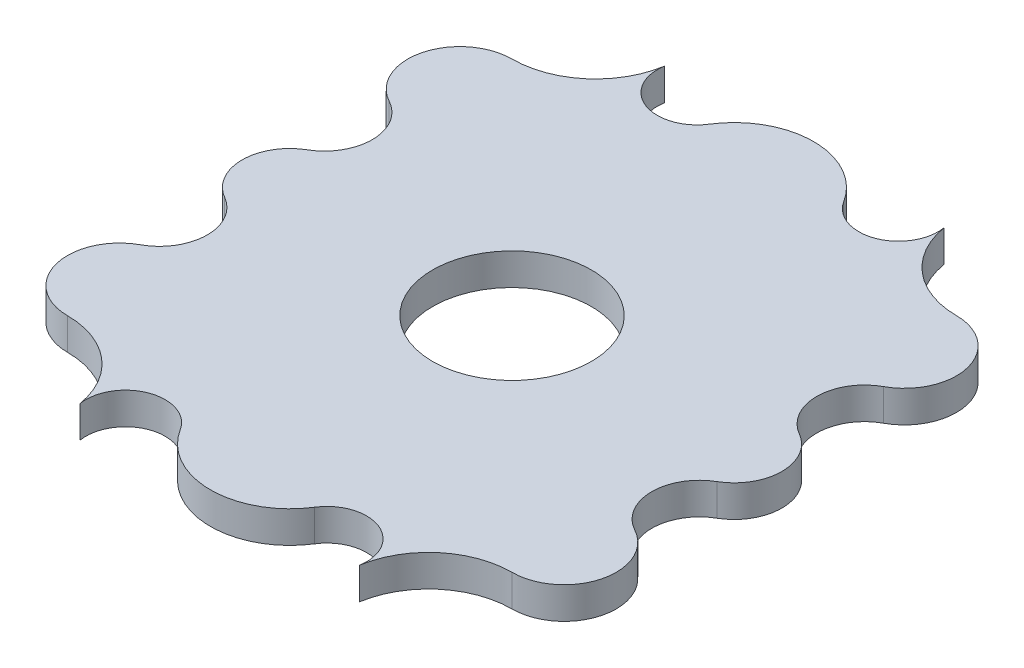
SolidWorks part; units mm, degrees
ref_plane "Alzado" through (0, 0, 0) normal (0, 0, 1) x (1, 0, 0)
ref_plane "Planta" through (0, 0, 0) normal (0, 1, 0) x (1, 0, 0)
ref_plane "Vista lateral" through (0, 0, 0) normal (1, 0, 0) x (0, 0, -1)
sketch "Croquis1" plane through (0, 0, 0) normal (0, 1, 0) x (1, 0, 0)
  line L0 (0, 138.5041) -> (0, -177.2184) construction
  line L2 (-70, -70) -> (-70, 70)
  line L4 (70, -70) -> (70, 70)
  line L5 (-70, -70) -> (70, 70) construction
  line L6 (-70, 70) -> (70, -70) construction
  line L7 (-103.4324, 0) -> (144.2109, 0) construction
  arc A1 (-21.1476, -83.3333) -> (21.1476, -83.3333) centre (0, -70) ccw
  arc A5 (-21.1476, -83.3333) -> (-44.0559, -92.0276) centre (-31.7214, -90) ccw
  arc A6 (-44.0559, -92.0276) -> (-70, -70) centre (-70, -96.2923) ccw
  arc A7 (21.1476, -83.3333) -> (44.0559, -92.0276) centre (31.7214, -90) cw
  arc A8 (44.0559, -92.0276) -> (70, -70) centre (70, -96.2923) cw
  arc A9 (44.0559, 92.0276) -> (70, 70) centre (70, 96.2923) ccw
  arc A10 (21.1476, 83.3333) -> (44.0559, 92.0276) centre (31.7214, 90) ccw
  arc A11 (-21.1476, 83.3333) -> (21.1476, 83.3333) centre (0, 70) cw
  arc A12 (-21.1476, 83.3333) -> (-44.0559, 92.0276) centre (-31.7214, 90) cw
  arc A13 (-44.0559, 92.0276) -> (-70, 70) centre (-70, 96.2923) cw
  point P0 (0, 0)
  point P14 (-25, -70)
  point P16 (-70, -70)
  dimension "D4" = 50
  dimension "D6" = 25
  dimension "D1" = 140
  dimension "D2" = 140
extrude "Saliente-Extruir1" add sketch "Croquis1" along normal blind 10
sketch "Croquis2" plane through (0, 10, 0) normal (0, 1, 0) x (1, 0, 0)
  line L0 (70, -70) -> (70, 70) construction
  line L1 (70, 70) -> (70, -70)
  line L2 (0, 152.4123) -> (0, -148.5895) construction
  line L3 (-96.3545, 0) -> (168.0513, 0) construction
  line L4 (-70, 70) -> (-70, -70)
  arc A0 (77.5, -12.9904) -> (77.5, 12.9904) centre (70, 0) ccw
  arc A1 (77.838, 39.1605) -> (77.5, 12.9904) centre (85, 25.9808) ccw
  arc A2 (77.838, 39.1605) -> (70, 70) centre (70, 53.5842) ccw
  arc A3 (77.838, -39.1605) -> (77.5, -12.9904) centre (85, -25.9808) cw
  arc A4 (77.838, -39.1605) -> (70, -70) centre (70, -53.5842) cw
  arc A5 (-77.838, -39.1605) -> (-70, -70) centre (-70, -53.5842) ccw
  arc A6 (-77.838, -39.1605) -> (-77.5, -12.9904) centre (-85, -25.9808) ccw
  arc A7 (-77.5, -12.9904) -> (-77.5, 12.9904) centre (-70, 0) cw
  arc A8 (-77.838, 39.1605) -> (-77.5, 12.9904) centre (-85, 25.9808) cw
  arc A9 (-77.838, 39.1605) -> (-70, 70) centre (-70, 53.5842) cw
  line M11 (-70, 70) -> (-70, -70)
  line M17 (70, -70) -> (70, 70)
  dimension "D1" = 30
  dimension "D2" = 30
extrude "Saliente-Extruir2" add sketch "Croquis2" against normal blind 10 contours A9 A8 M11 | A1 A2 L1 | L1 A3 A0 A1 | L4 A8 A7 A6 | A6 A5 L4 | A4 A3 M17
sketch "Croquis3" plane through (0, 10, 0) normal (0, 1, 0) x (1, 0, 0)
  circle A0 centre (0, 0) radius 25
  dimension "D1" = 50
extrude "Cortar-Extruir1" cut sketch "Croquis3" against normal blind 10
